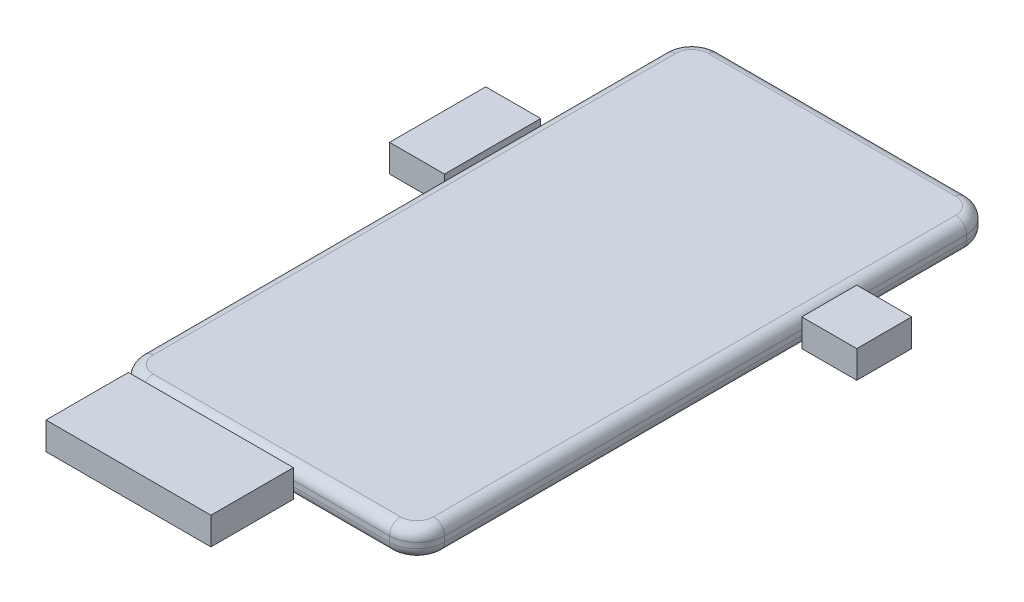
SolidWorks part; units mm, degrees
ref_plane "Front Plane" through (0, 0, 0) normal (0, 0, 1) x (1, 0, 0)
ref_plane "Top Plane" through (0, 0, 0) normal (0, 1, 0) x (1, 0, 0)
ref_plane "Right Plane" through (0, 0, 0) normal (1, 0, 0) x (0, 0, -1)
sketch "Sketch1" plane through (0, 0, 0) normal (0, 1, 0) x (1, 0, 0)
  line L1 (0, 0) -> (69.85, 0)
  line L2 (0, 0) -> (0, 133.35)
  line L3 (0, 133.35) -> (69.85, 133.35)
  line L4 (69.85, 0) -> (69.85, 133.35)
  dimension "D1" = 69.85
  dimension "D2" = 133.35
extrude "Boss-Extrude1" add sketch "Sketch1" along normal blind 6.35
fillet "Fillet2" radius 6.35 4 edges at (0, 3.175, -133.35) (69.85, 3.175, -133.35) (0, 3.175, 0) (69.85, 3.175, 0)
fillet "Fillet3" radius 2.54 16 edges at (67.9901, 0, -1.8599) (34.925, 0, 0) (1.8599, 0, -1.8599) (0, 0, -66.675) (1.8599, 0, -131.4901) (34.925, 0, -133.35) (67.9901, 0, -131.4901) (67.9901, 6.35, -1.8599) (34.925, 6.35, 0) (1.8599, 6.35, -1.8599) (0, 6.35, -66.675) (1.8599, 6.35, -131.4901) (34.925, 6.35, -133.35) (67.9901, 6.35, -131.4901) (69.85, 0, -66.675) (69.85, 6.35, -66.675)
sketch "Sketch2" plane through (0, 0, 0) normal (0, 1, 0) x (1, 0, 0)
  line L0 (6.35, 133.35) -> (63.5, 133.35) construction
  line L1 (69.85, 101.6) -> (82.55, 101.6)
  line L2 (69.85, 101.6) -> (69.85, 88.9)
  line L3 (69.85, 88.9) -> (82.55, 88.9)
  line L4 (82.55, 101.6) -> (82.55, 88.9)
  line L5 (0, 98.425) -> (-12.7, 98.425)
  line L6 (0, 98.425) -> (0, 76.2)
  line L7 (0, 76.2) -> (-12.7, 76.2)
  line L8 (-12.7, 98.425) -> (-12.7, 76.2)
  line L9 (0, 6.35) -> (0, 127) construction
  line L10 (69.85, 127) -> (69.85, 6.35) construction
  dimension "D1" = 31.75
  dimension "D2" = 44.45
  dimension "D3" = 57.15
  dimension "D4" = 34.925
  dimension "D5" = 12.7
  dimension "D6" = 12.7
extrude "buttons" add sketch "Sketch2" along normal blind 6.35 separate body
sketch "Sketch3" plane through (0, 0, 0) normal (0, -1, 0) x (1, 0, 0)
  line L0 (63.5, -133.35) -> (6.35, -133.35) construction
  line L1 (12.7, -107.95) -> (57.15, -107.95)
  line L2 (12.7, -107.95) -> (12.7, -127)
  line L3 (12.7, -127) -> (57.15, -127)
  line L4 (57.15, -107.95) -> (57.15, -127)
  line L5 (69.85, -6.35) -> (69.85, -127) construction
  line L6 (0, -127) -> (0, -6.35) construction
  dimension "D1" = 25.4
  dimension "D2" = 19.05
  dimension "D3" = 12.7
  dimension "D4" = 12.7
extrude "camera" add sketch "Sketch3" along normal blind 6.35 separate body
sketch "Sketch4" plane through (0, 0, 0) normal (0, 1, 0) x (1, 0, 0)
  line L0 (63.5, 0) -> (6.35, 0) construction
  line L1 (3.175, -19.05) -> (41.275, -19.05)
  line L2 (3.175, -19.05) -> (3.175, 0)
  line L3 (3.175, 0) -> (41.275, 0)
  line L4 (41.275, -19.05) -> (41.275, 0)
  line L5 (69.85, 127) -> (69.85, 6.35) construction
  dimension "D1" = 28.575
  dimension "D2" = 38.1
  dimension "D3" = 19.05
extrude "USB" add sketch "Sketch4" along normal blind 6.35 separate body
ref_plane "centerline" through (34.925, 0, 0) normal (1, 0, 0) x (0, 0, -1)
